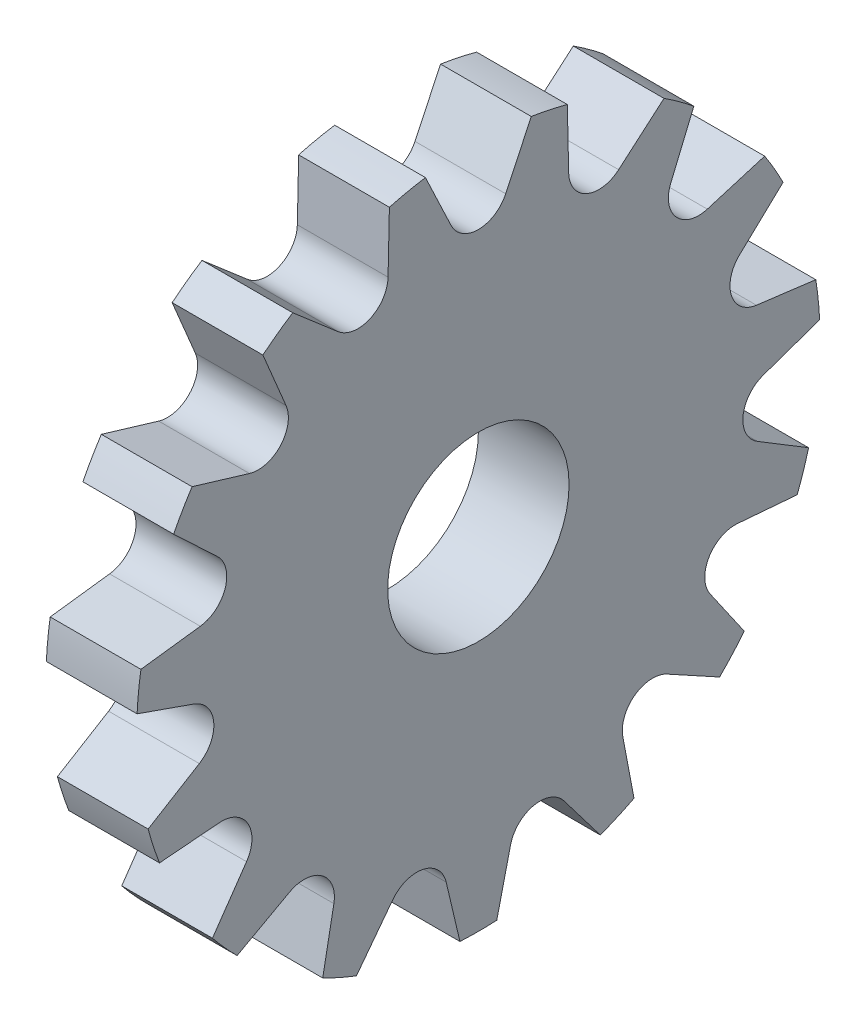
SolidWorks part; units mm, degrees
material "Plain Carbon Steel"
ref_plane "Front Plane" through (0, 0, 0) normal (0, 0, 1) x (1, 0, 0)
ref_plane "Top Plane" through (0, 0, 0) normal (0, 1, 0) x (1, 0, 0)
ref_plane "Right Plane" through (0, 0, 0) normal (1, 0, 0) x (0, 0, -1)
sketch "Sketch1" plane through (0, 0, 0) normal (1, 0, 0) x (0, 0, -1)
  circle A0 centre (0, 0) radius 22.6
  circle A1 centre (0, 0) radius 6
  dimension "D1" = 12
  dimension "D2" = 45.2
extrude "Boss-Extrude1" add sketch "Sketch1" along normal blind 6
sketch "Sketch2" plane through (6, 0, 0) normal (1, 0, 0) x (0, 0, -1)
  line L0 (0, 0) -> (0, 22.6) construction
  line L1 (-3.5, 22.3273) -> (-1.8084, 18.7459)
  line L2 (1.8084, 18.7459) -> (3.5, 22.3273)
  line L3 (3.5, 22.3273) -> (0, 25.8273)
  line L4 (0, 25.8273) -> (-3.5, 22.3273)
  line L5 (0, 22.6) -> (0, 26.6413) construction
  line L6 (-3.5, 22.3273) -> (3.5, 22.3273) construction
  circle A0 centre (0, 0) radius 22.6 construction
  arc A1 (-1.8084, 18.7459) -> (1.8084, 18.7459) centre (0, 19.6) ccw
  point P13 (0, 14.9169)
  dimension "D3" = 2
  dimension "D1" = 7
  dimension "D2" = 3
extrude "Cut-Extrude1" cut sketch "Sketch2" against normal blind 6
pattern_circular "CirPattern1" count 15 over 360 about axis through (0, 0, 0) along (1, 0, 0) of "Cut-Extrude1"
